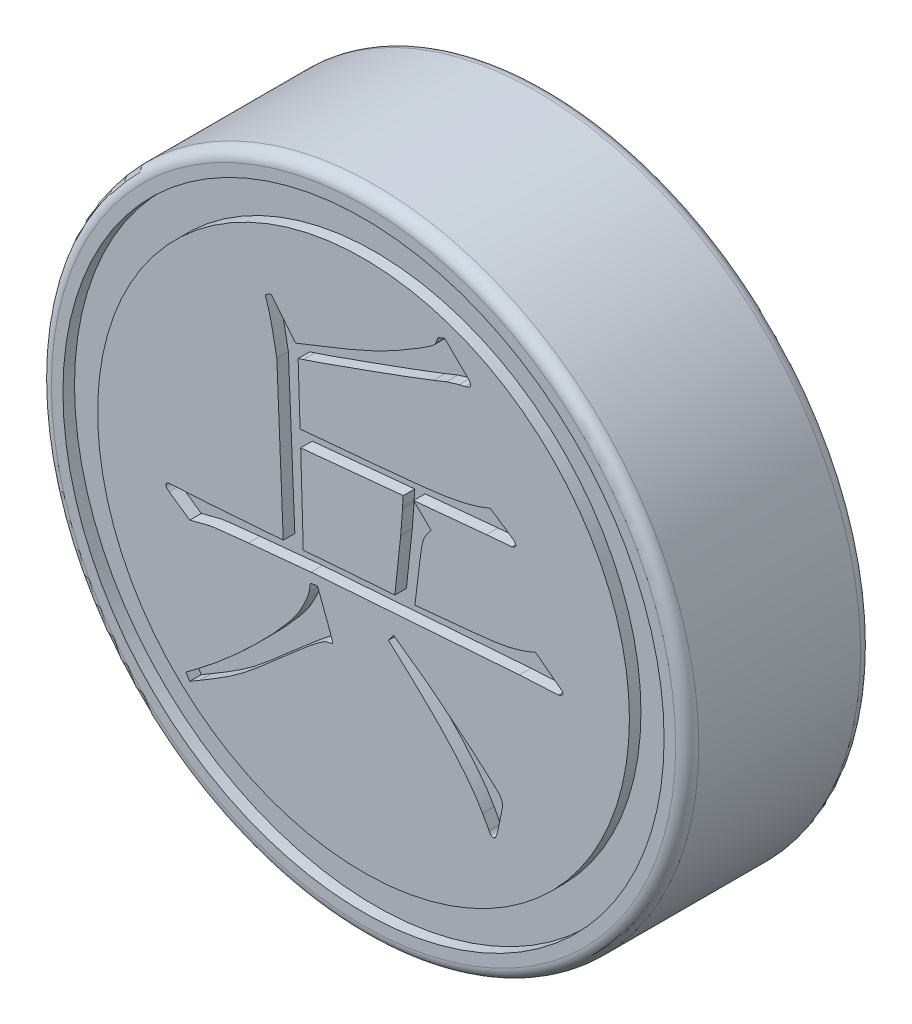
SolidWorks part; units mm, degrees
ref_plane "前视基准面" through (0, 0, 0) normal (0, 0, 1) x (1, 0, 0)
ref_plane "上视基准面" through (0, 0, 0) normal (0, 1, 0) x (1, 0, 0)
ref_plane "右视基准面" through (0, 0, 0) normal (1, 0, 0) x (0, 0, -1)
sketch "草图1" plane through (0, 0, 0) normal (0, 0, 1) x (1, 0, 0)
  circle A0 centre (0, 0) radius 14
extrude "凸台-拉伸1" add sketch "草图1" along normal blind 8
sketch "草图2" plane through (0, 0, 8) normal (0, 0, 1) x (1, 0, 0)
  circle A0 centre (0, 0) radius 13
  circle A1 centre (0, 0) radius 11.5
extrude "切除-拉伸1" cut sketch "草图2" against normal blind 0.5
sketch "草图3" plane through (0, 0, 0) normal (0, 0, -1) x (-1, 0, 0)
  circle A0 centre (0, 0) radius 5.1
extrude "切除-拉伸2" cut sketch "草图3" against normal blind 5
chamfer "倒角1" distance 0.5 angle 45 1 edges at (-5.1, 0, 0)
fillet "圆角1" radius 0.5 2 edges at (14, 0, 8) (14, 0, 0)
sketch "草图4" plane through (0, 0, 8) normal (0, 0, 1) x (1, 0, 0)
  text T0 "兵" font "汉仪长仿宋体" height 13
extrude "切除-拉伸3" cut sketch "草图4" against normal blind 0.5
